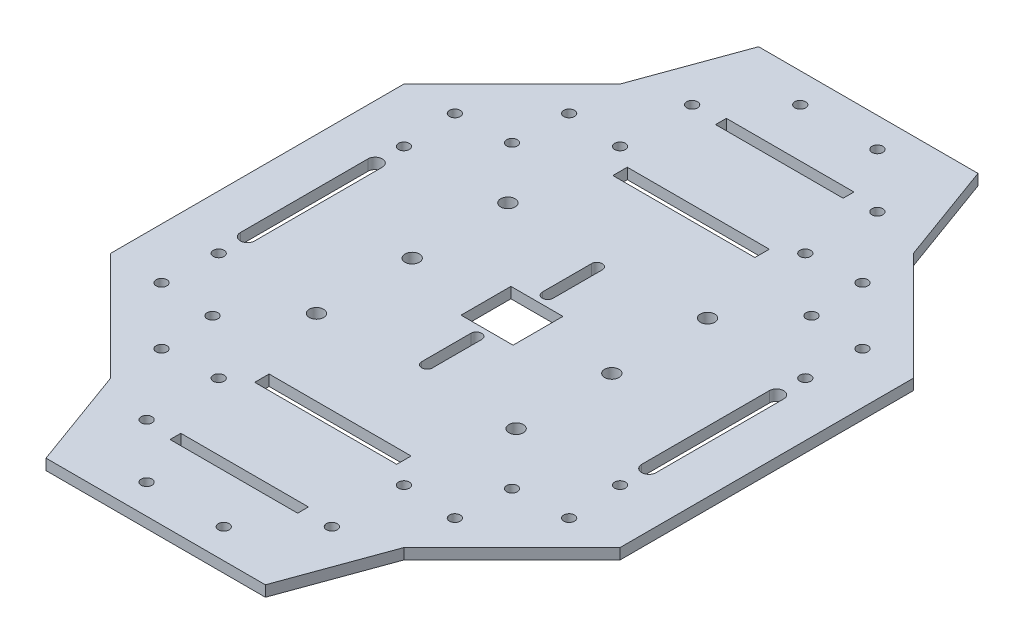
SolidWorks part; units mm, degrees
ref_plane "前视基准面" through (0, 0, 0) normal (0, 0, 1) x (1, 0, 0)
ref_plane "上视基准面" through (0, 0, 0) normal (0, 1, 0) x (1, 0, 0)
ref_plane "右视基准面" through (0, 0, 0) normal (1, 0, 0) x (0, 0, -1)
other "Configuration Table"
sketch "草图1" plane through (0, 0, 0) normal (0, 1, 0) x (1, 0, 0)
  line L0 (-70.7107, -70.7107) -> (70.7107, -70.7107)
  line L3 (70.7107, -70.7107) -> (70.7107, 70.7107)
  line L4 (70.7107, 70.7107) -> (-70.7107, 70.7107)
  line L5 (-70.7107, 70.7107) -> (-70.7107, -70.7107)
extrude "凸台-拉伸1" add sketch "草图1" along normal blind 3
sketch "草图2" plane through (0, 0, 0) normal (0, 1, 0) x (1, 0, 0)
  line L0 (-70.7107, 70.7107) -> (-40.7107, 70.7107)
  line L1 (70.7107, 70.7107) -> (-70.7107, 70.7107) construction
  line L2 (-70.7107, 70.7107) -> (-70.7107, 40.7107)
  line L3 (-70.7107, 70.7107) -> (-70.7107, -70.7107) construction
  line L4 (-40.7107, 70.7107) -> (-70.7107, 40.7107)
extrude "切除-拉伸1" cut sketch "草图2" along normal blind 3
mirror "镜向1" about plane through (0, 0, 0) normal (1, 0, 0) of "切除-拉伸1" second plane through (0, 0, 0) second plane normal (0, 0, 1)
sketch "草图3" plane through (0, 0, 0) normal (0, 1, 0) x (1, 0, 0)
  circle A0 centre (-56.5685, 40.7107) radius 1.5
  circle A1 centre (-40.7107, 56.5685) radius 1.5
  circle A2 centre (-41.5685, 41.5685) radius 1.5
extrude "切除-拉伸2" cut sketch "草图3" along normal blind 3
mirror "镜向2" about plane through (0, 0, 0) normal (0, 0, 1) of "切除-拉伸2" second plane through (0, 0, 0) second plane normal (1, 0, 0)
sketch "草图4" plane through (0, 0, 0) normal (0, 1, 0) x (1, 0, 0)
  circle A0 centre (-27.7107, 26.5685) radius 2
  circle A1 centre (-27.7107, -26.5685) radius 2
  circle A2 centre (-27.7107, 0) radius 2
extrude "切除-拉伸3" cut sketch "草图4" along normal blind 3
mirror "镜向3" about plane through (0, 0, 0) normal (1, 0, 0) of "切除-拉伸3"
sketch "草图5" plane through (0, 0, 0) normal (0, 1, 0) x (1, 0, 0)
  circle A0 centre (-55.7107, 25.7107) radius 1.5
extrude "切除-拉伸4" cut sketch "草图5" along normal blind 3
mirror "镜向4" about plane through (0, 0, 0) normal (1, 0, 0) of "切除-拉伸4" second plane through (0, 0, 0) second plane normal (0, 0, 1)
sketch "草图6" plane through (0, 0, 0) normal (0, 1, 0) x (1, 0, 0)
  circle A0 centre (-25.7107, 55.7107) radius 1.5
extrude "切除-拉伸5" cut sketch "草图6" along normal blind 3
mirror "镜向5" about plane through (0, 0, 0) normal (0, 0, 1) of "切除-拉伸5" second plane through (0, 0, 0) second plane normal (1, 0, 0)
sketch "草图7" plane through (0, 0, 0) normal (0, 1, 0) x (1, 0, 0)
  line L3 (-55.7107, 17.7107) -> (-55.7107, -17.7107) construction
  line L4 (-53.7107, 17.7107) -> (-53.7107, -17.7107)
  line L5 (-57.7107, 17.7107) -> (-57.7107, -17.7107)
  arc A0 (-53.7107, 17.7107) -> (-57.7107, 17.7107) centre (-55.7107, 17.7107) ccw
  arc A1 (-57.7107, -17.7107) -> (-53.7107, -17.7107) centre (-55.7107, -17.7107) ccw
  point P4 (-55.7107, 0)
extrude "切除-拉伸6" cut sketch "草图7" along normal blind 3
mirror "镜向6" about plane through (0, 0, 0) normal (1, 0, 0) of "切除-拉伸6"
sketch "草图8" plane through (0, 0, 0) normal (0, 1, 0) x (1, 0, 0)
  line L3 (7.2183, 6.9207) -> (-7.2183, 6.9207)
  line L4 (-7.2183, 6.9207) -> (-7.2183, -6.9207)
  line L5 (-7.2183, -6.9207) -> (7.2183, -6.9207)
  line L6 (7.2183, -6.9207) -> (7.2183, 6.9207)
extrude "切除-拉伸7" cut sketch "草图8" along normal blind 3
sketch "草图9" plane through (0, 0, 0) normal (0, 1, 0) x (1, 0, 0)
  line L5 (0, -9.9207) -> (0, -23.5685) construction
  line L6 (1.5, -9.9207) -> (1.5, -23.5685)
  line L7 (-1.5, -9.9207) -> (-1.5, -23.5685)
  arc A0 (1.5, -9.9207) -> (-1.5, -9.9207) centre (0, -9.9207) ccw
  arc A1 (-1.5, -23.5685) -> (1.5, -23.5685) centre (0, -23.5685) ccw
  point P10 (0, -16.7446)
extrude "切除-拉伸8" cut sketch "草图9" along normal blind 3
mirror "镜向7" about plane through (0, 0, 0) normal (0, 0, 1) of "切除-拉伸8"
sketch "草图10" plane through (0, 0, 0) normal (0, 1, 0) x (1, 0, 0)
  line L0 (-19.7107, 51.7107) -> (-19.7107, 51.4904)
  line L4 (-19.7107, 51.7107) -> (19.7107, 51.7107)
  line L5 (19.7107, 51.7107) -> (19.7107, 47.7107)
  line L6 (19.7107, 47.7107) -> (-19.7107, 47.7107)
  line L7 (-19.7107, 47.7107) -> (-19.7107, 51.4904)
extrude "切除-拉伸10" cut sketch "草图10" along normal blind 3
mirror "镜向8" about plane through (0, 0, 0) normal (0, 0, 1) of "切除-拉伸10"
sketch "草图11" plane through (0, 3, 0) normal (0, 1, 0) x (1, 0, 0)
  line L0 (-40.7107, 70.7107) -> (-30.4501, 98.9015)
  line L1 (40.7107, 70.7107) -> (30.4501, 98.9015)
  line L3 (-30.4501, 98.9015) -> (30.4501, 98.9015)
  line L4 (-40.7107, 70.7107) -> (40.7107, 70.7107)
extrude "凸台-拉伸2" add sketch "草图11" against normal blind 3
mirror "镜向9" about plane through (0, 0, 0) normal (1, 0, 0) of "凸台-拉伸2" second plane through (0, 0, 0) second plane normal (0, 0, 1)
sketch "草图13" plane through (0, 0, 0) normal (0, -1, 0) x (1, 0, 0)
  line L6 (-17.7107, 75.7107) -> (-17.7107, 77.2107)
  line L7 (-17.7107, 75.7107) -> (-17.7107, 74.2107)
  line L8 (-17.7107, 74.2107) -> (0, 74.2107)
  line L9 (0, 74.2107) -> (0, 77.2107)
  line L10 (0, 77.2107) -> (-17.7107, 77.2107)
  circle A0 centre (-25.7107, 75.7107) radius 1.5
  circle A1 centre (-10.7107, 90.7107) radius 1.5
extrude "切除-拉伸11" cut sketch "草图13" against normal blind 3
mirror "镜向10" about plane through (0, 0, 0) normal (1, 0, 0) of "切除-拉伸11"
mirror "镜向11" about plane through (0, 0, 0) normal (0, 0, 1) of "镜向10", "切除-拉伸11"
sketch "草图14" plane through (0, 3, 0) normal (0, 1, 0) x (1, 0, 0)
  line L2 (-70.7107, 40.7107) -> (-48.053, 30.1452)
  line L3 (-40.7107, 70.7107) -> (-30.1452, 48.053)
  line L4 (-70.7107, 40.7107) -> (-40.7107, 70.7107) construction
  line L5 (-48.053, 30.1452) -> (-30.1452, 48.053)
  line L11 (-55.7107, 25.7107) -> (-55.7107, -25.7107)
  line L12 (-55.7107, 25.7107) -> (-55.7107, 36.7107)
  line L13 (-55.7107, 36.7107) -> (-40.7107, 36.7107)
  line L14 (-55.7107, 36.7107) -> (-70.7107, 36.7107)
  line L15 (-70.7107, 40.7107) -> (-70.7107, -40.7107) construction
  line L16 (-55.7107, -25.7107) -> (-55.7107, -36.7107)
  line L17 (-55.7107, -36.7107) -> (-70.7107, -36.7107)
  line L18 (-55.7107, -36.7107) -> (-40.7107, -36.7107)
  line L19 (-40.7107, -36.7107) -> (-40.7107, 36.7107)
  dimension "D1" = 70
  dimension "D2" = 70
